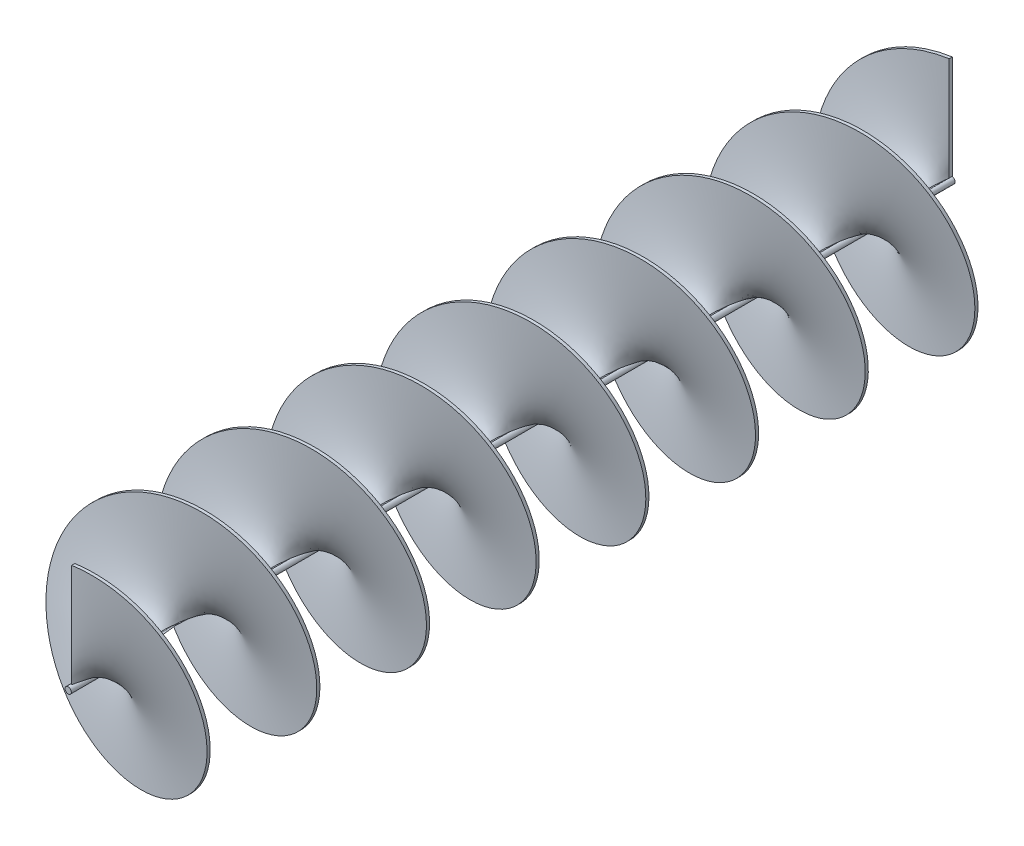
SolidWorks part; units mm, degrees
ref_plane "前视基准面" through (0, 0, 0) normal (0, 0, 1) x (1, 0, 0)
ref_plane "上视基准面" through (0, 0, 0) normal (0, 1, 0) x (1, 0, 0)
ref_plane "右视基准面" through (0, 0, 0) normal (1, 0, 0) x (0, 0, -1)
sketch "草图1" plane through (0, 0, 0) normal (0, 0, 1) x (1, 0, 0)
  circle A0 centre (0, 0) radius 1
extrude "凸台-拉伸1" add sketch "草图1" along normal blind 282
sketch "草图2" plane through (0, 0, 0) normal (0, 0, -1) x (-1, 0, 0)
  circle A1 centre (0, 0) radius 1
  circle A2 centre (0, 0) radius 1
  dimension "D1" = 0
curve "螺旋线/涡状线1" pitch 35 height 280 turns 8
sketch "草图4" plane through (0, 0, 0) normal (0, 0, -1) x (-1, 0, 0)
  line L0 (0, 0) -> (0, 1.0461)
sketch "草图5" plane through (0, 0, 282) normal (0, 0, 1) x (1, 0, 0)
  line L0 (0, 0) -> (0, 1.0461)
ref_plane "基准面4" through (0, 0, 0) normal (1, 0, 0) x (0, 0, -1)
sketch "草图6" plane through (0, 0, 0) normal (1, 0, 0) x (0, 0, -1)
  line L0 (0, 1) -> (-282, 1) construction
  line L1 (0.1085, 34) -> (-0.8915, 34)
  line L2 (0.1085, 34) -> (0.1085, 1)
  line L3 (0.1085, 1) -> (-0.8915, 1)
  line L4 (-0.8915, 34) -> (-0.8915, 1)
  dimension "D1" = 33
  dimension "D2" = 1
sweep "扫描1" add profiles "草图6" path "螺旋线/涡状线1"
